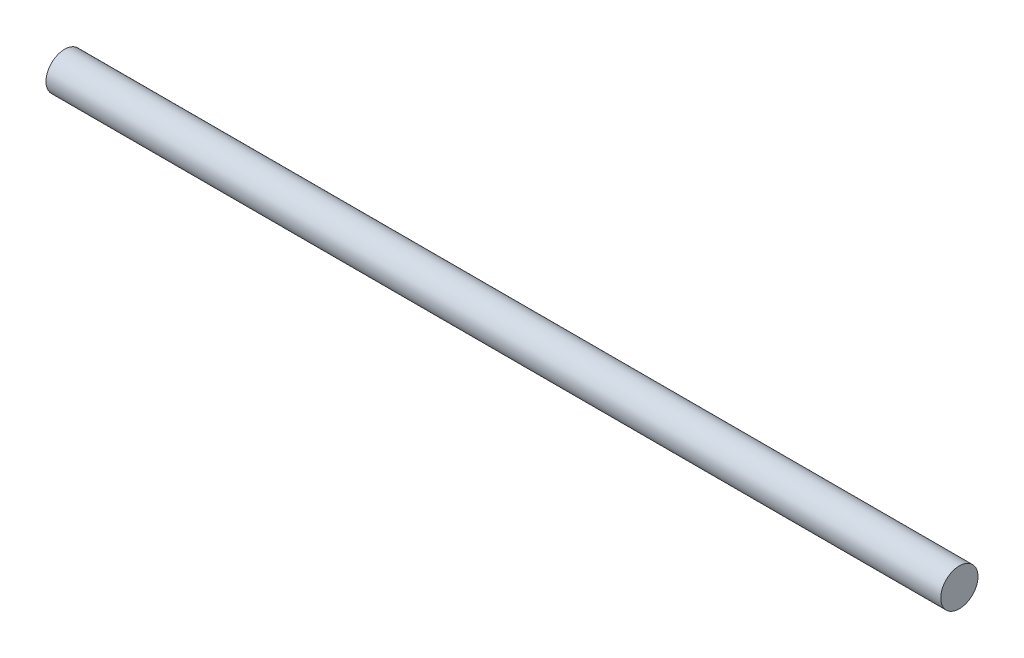
SolidWorks part; units mm, degrees
material "1023 碳钢板 (SS)"
ref_plane "前视基准面" through (0, 0, 0) normal (0, 0, 1) x (1, 0, 0)
ref_plane "上视基准面" through (0, 0, 0) normal (0, 1, 0) x (1, 0, 0)
ref_plane "右视基准面" through (0, 0, 0) normal (1, 0, 0) x (0, 0, -1)
other "Configuration Table"
sketch "草图1" plane through (0, 0, 0) normal (1, 0, 0) x (0, 0, -1)
  circle A0 centre (0, 0) radius 2.5
  dimension "D1" = 5
extrude "凸台-拉伸1" add sketch "草图1" along normal blind 120
